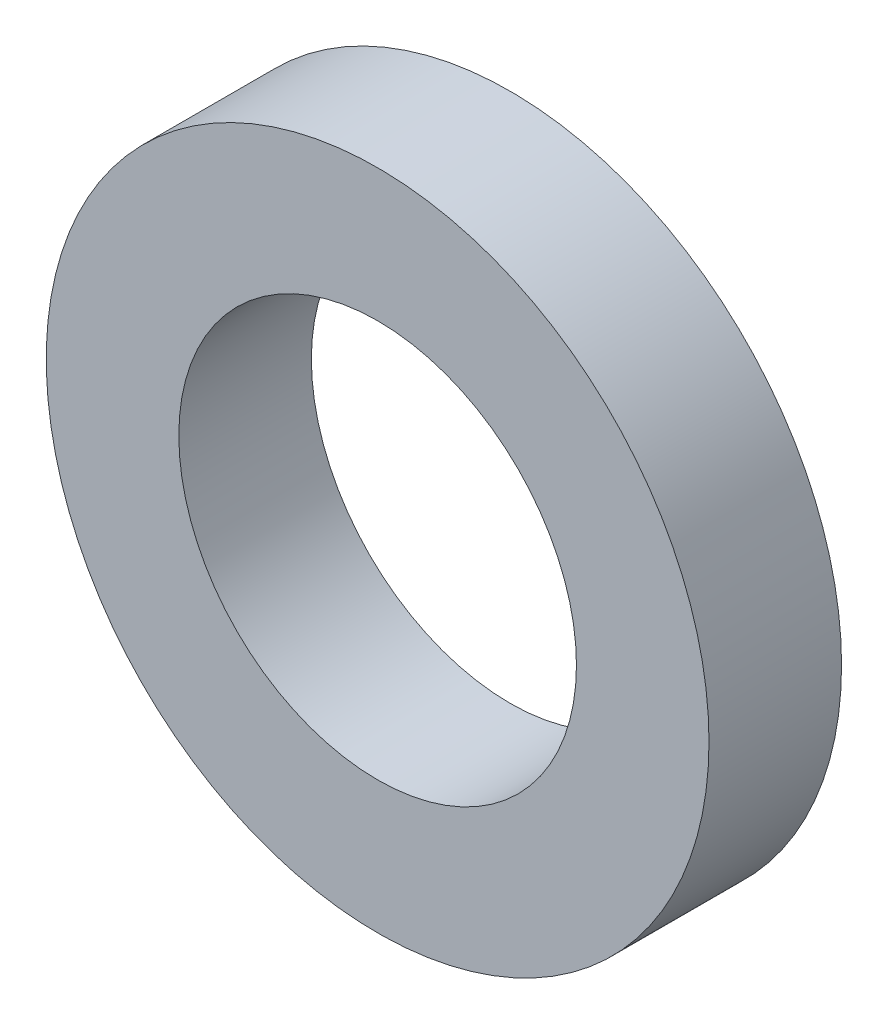
SolidWorks part; units mm, degrees
ref_plane "Front Plane" through (0, 0, 0) normal (0, 0, 1) x (1, 0, 0)
ref_plane "Top Plane" through (0, 0, 0) normal (0, 1, 0) x (1, 0, 0)
ref_plane "Right Plane" through (0, 0, 0) normal (1, 0, 0) x (0, 0, -1)
sketch "Sketch1" plane through (0, 0, 0) normal (0, 0, 1) x (1, 0, 0)
  circle A0 centre (0, 0) radius 25
  circle A1 centre (0, 0) radius 15
  dimension "D1" = 50
  dimension "D2" = 30
extrude "Boss-Extrude1" add sketch "Sketch1" along normal blind 10
